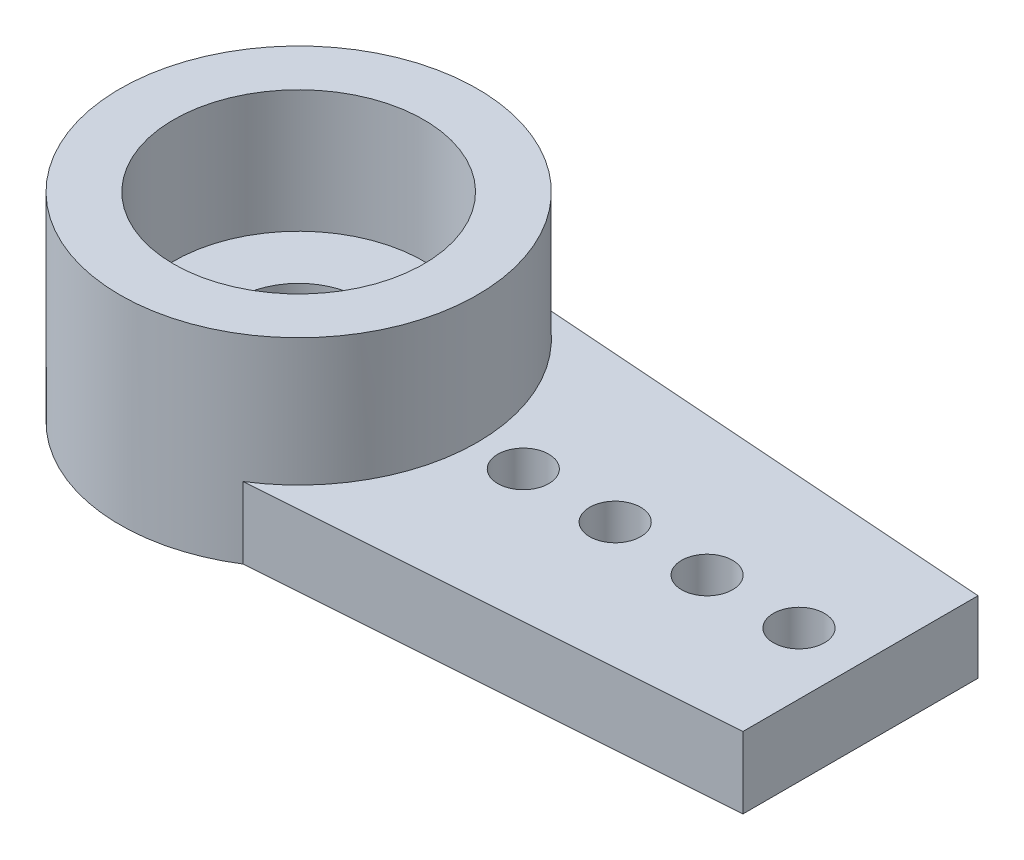
SolidWorks part; units mm, degrees
other "Camera1"
material "ABS"
ref_plane "Front Plane" through (0, 0, 0) normal (0, 0, 1) x (1, 0, 0)
ref_plane "Top Plane" through (0, 0, 0) normal (0, 1, 0) x (1, 0, 0)
ref_plane "Right Plane" through (0, 0, 0) normal (1, 0, 0) x (0, 0, -1)
sketch "Sketch1" plane through (0, 0, 0) normal (0, 1, 0) x (1, 0, 0)
  line L0 (-17.2, 0) -> (11.0049, 0) construction
  line L1 (0, -8.35) -> (0, 8.35) construction
  line L2 (-15.2, 2) -> (-2, 2.95)
  line L3 (-15.2, -2) -> (-2, -2.95)
  line L4 (2, 6.35) -> (2, 3.5)
  line L5 (-2, 6.35) -> (-2, 2.95)
  line L6 (2, -6.35) -> (2, -3.5)
  line L7 (-2, -6.35) -> (-2, -2.95)
  line L8 (11.0049, 2.4767) -> (2, 3.5)
  line L9 (11.0049, -2.4767) -> (2, -3.5)
  line L10 (11.0049, 2.4767) -> (11.0049, -2.4767)
  circle A0 centre (0, 0) radius 3.5 construction
  arc A1 (-15.2, 2) -> (-15.2, -2) centre (-15.2, 0) ccw
  arc A3 (2, 6.35) -> (-2, 6.35) centre (0, 6.35) ccw
  circle A4 centre (0, 6.35) radius 0.5
  circle A5 centre (0, 4.55) radius 0.5
  circle A6 centre (0, -4.55) radius 0.5
  circle A7 centre (0, -6.35) radius 0.5
  arc A8 (2, -6.35) -> (-2, -6.35) centre (0, -6.35) cw
  circle A10 centre (-15.2, 0) radius 0.5
  circle A12 centre (-13.4, 0) radius 0.5
  circle A13 centre (-11.6, 0) radius 0.5
  circle A14 centre (-9.8, 0) radius 0.5
  circle A15 centre (-8, 0) radius 0.5
  circle A16 centre (-6.2, 0) radius 0.5
  circle A17 centre (-4.4, 0) radius 0.5
  circle A20 centre (9.8, 0) radius 0.5
  circle A21 centre (8, 0) radius 0.5
  circle A22 centre (6.2, 0) radius 0.5
  circle A23 centre (4.4, 0) radius 0.5
  point P8 (0, 0)
  point P25 (0, 6.85)
  point P26 (0, 4.05)
  dimension "D1" = 7
  dimension "D4" = 4
  dimension "D6" = 1
  dimension "D3" = 16.7
  dimension "D5" = 2
  dimension "D7" = 2.8
  dimension "D8" = 7
  dimension "D10" = 5.9
  dimension "D11" = 7
extrude "Boss-Extrude1" add sketch "Sketch1" along normal blind 1.4
sketch "Sketch2" plane through (0, 0, 0) normal (0, -1, 0) x (1, 0, 0)
  circle A0 centre (0, 0) radius 2.35
  dimension "D1" = 4.7
extrude "Cut-Extrude1" cut sketch "Sketch2" against normal blind 1
sketch "Sketch3" plane through (0, 1.4, 0) normal (0, 1, 0) x (1, 0, 0)
  circle A0 centre (0, 0) radius 2.45
  circle A1 centre (0, 0) radius 3.5
  dimension "D1" = 4.9
  dimension "D2" = 7
extrude "Boss-Extrude2" add sketch "Sketch3" along normal blind 2.5
sketch "Sketch4" plane through (0, 1.4, 0) normal (0, 1, 0) x (1, 0, 0)
  circle A0 centre (0, 0) radius 1.2
  dimension "D1" = 2.4
extrude "Cut-Extrude2" cut sketch "Sketch4" against normal through all
sketch "Sketch5" plane through (0, 1.4, 0) normal (0, 1, 0) x (1, 0, 0)
  circle A0 centre (0, 0) radius 1.2 construction
  circle A1 centre (0, 0) radius 2.45
  circle A2 centre (0, 0) radius 2.45
  circle A3 centre (0, 0) radius 1.2
  dimension "D1" = 0
extrude "Boss-Extrude3" add sketch "Sketch5" along normal blind 0.1
sketch "Sketch6" plane through (0, 0, 0) normal (0, -1, 0) x (1, 0, 0)
  line L0 (-2, -2.95) -> (-15.2, -2) construction
  line L1 (-1.8686, -2.9595) -> (-15.2, -2)
  line L2 (-15.2, 2) -> (-2, 2.95) construction
  line L3 (-15.2, 2) -> (-1.8686, 2.9595)
  line L4 (0, -9.3016) -> (0, 8.6978) construction
  line L5 (1.8686, -2.9595) -> (15.2, -2)
  line L6 (15.2, 2) -> (1.8686, 2.9595)
  line L8 (-17.8676, -8.836) -> (17.8676, -8.836)
  line L9 (-17.8676, -8.836) -> (-17.8676, 8.836)
  line L10 (-17.8676, 8.836) -> (17.8676, 8.836)
  line L11 (17.8676, -8.836) -> (17.8676, 8.836)
  line L12 (-17.8676, -8.836) -> (17.8676, 8.836) construction
  line L13 (-17.8676, 8.836) -> (17.8676, -8.836) construction
  arc A0 (-15.2, 2) -> (-15.2, -2) centre (-15.2, 0) ccw construction
  arc A1 (-15.2, 2) -> (-15.2, -2) centre (-15.2, 0) ccw
  circle A2 centre (0, 0) radius 3.5 construction
  arc A3 (1.8686, 2.9595) -> (-1.8686, 2.9595) centre (0, 0) ccw
  arc A4 (15.2, 2) -> (15.2, -2) centre (15.2, 0) cw
  arc A5 (-1.8686, -2.9595) -> (1.8686, -2.9595) centre (0, 0) ccw
extrude "Cut-Extrude4" cut sketch "Sketch6" against normal through all
sketch "Sketch7" plane through (0, 0, 0) normal (0, -1, 0) x (1, 0, 0)
  line L0 (0, 3.5) -> (-17.7318, 3.5)
  line L1 (-17.7318, 3.5) -> (-17.7318, -3.5)
  line L2 (-17.7318, -3.5) -> (0, -3.5)
  circle A0 centre (0, 0) radius 3.5 construction
  arc A1 (0, 3.5) -> (0, -3.5) centre (0, 0) ccw
extrude "Cut-Extrude5" cut sketch "Sketch7" against normal through all
